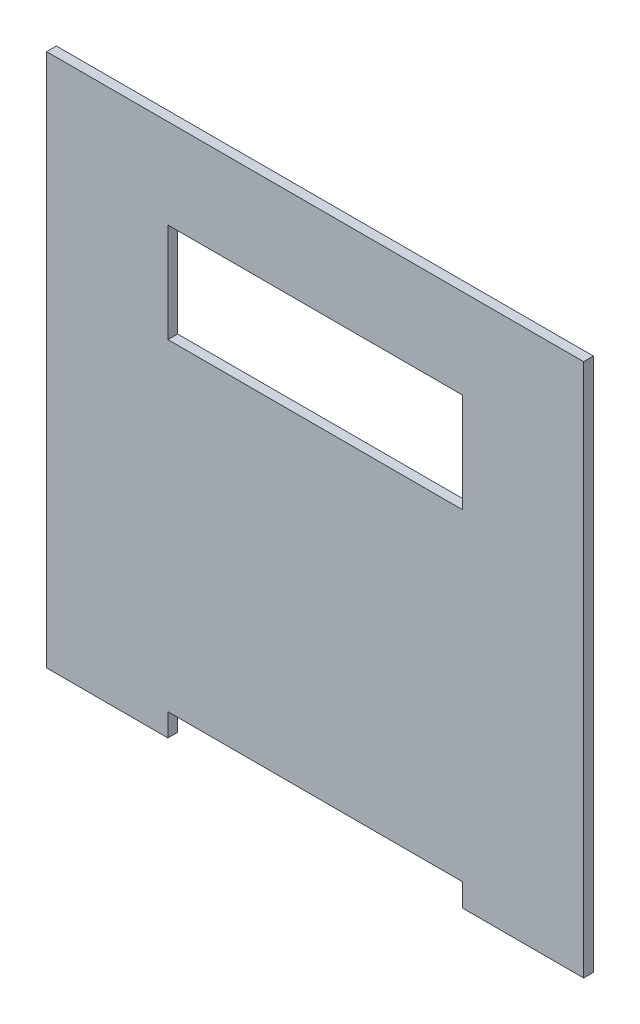
SolidWorks part; units mm, degrees
ref_plane "Plan de face" through (0, 0, 0) normal (0, 0, 1) x (1, 0, 0)
ref_plane "Plan de dessus" through (0, 0, 0) normal (0, 1, 0) x (1, 0, 0)
ref_plane "Plan de droite" through (0, 0, 0) normal (1, 0, 0) x (0, 0, -1)
sketch "Esquisse1" plane through (0, 0, 0) normal (0, 0, 1) x (1, 0, 0)
  line L1 (0, 0) -> (-330, 0)
  line L2 (0, 0) -> (0, 328)
  line L3 (0, 328) -> (-330, 328)
  line L4 (-330, 0) -> (-330, 328)
  dimension "D1" = 328
  dimension "D2" = 330
extrude "Boss.-Extru.1" add sketch "Esquisse1" along normal blind 6
sketch "Esquisse2" plane through (0, 0, 0) normal (0, 0, -1) x (-1, 0, 0)
  line L0 (330, 0) -> (0, 0) construction
  line L1 (74.5, 273) -> (255.5, 273)
  line L2 (74.5, 273) -> (74.5, 212)
  line L3 (74.5, 212) -> (255.5, 212)
  line L4 (255.5, 273) -> (255.5, 212)
  line L5 (74.5, 0) -> (255.5, 0)
  line L6 (74.5, 0) -> (74.5, 14)
  line L7 (74.5, 14) -> (255.5, 14)
  line L8 (255.5, 0) -> (255.5, 14)
  line L9 (330, 328) -> (330, 0) construction
  dimension "D1" = 61
  dimension "D2" = 181
  dimension "D3" = 74.5
  dimension "D4" = 14
  dimension "D5" = 181
  dimension "D6" = 74.5
  dimension "D7" = 212
extrude "Enlèv. mat.-Extru.1" cut sketch "Esquisse2" against normal through all
